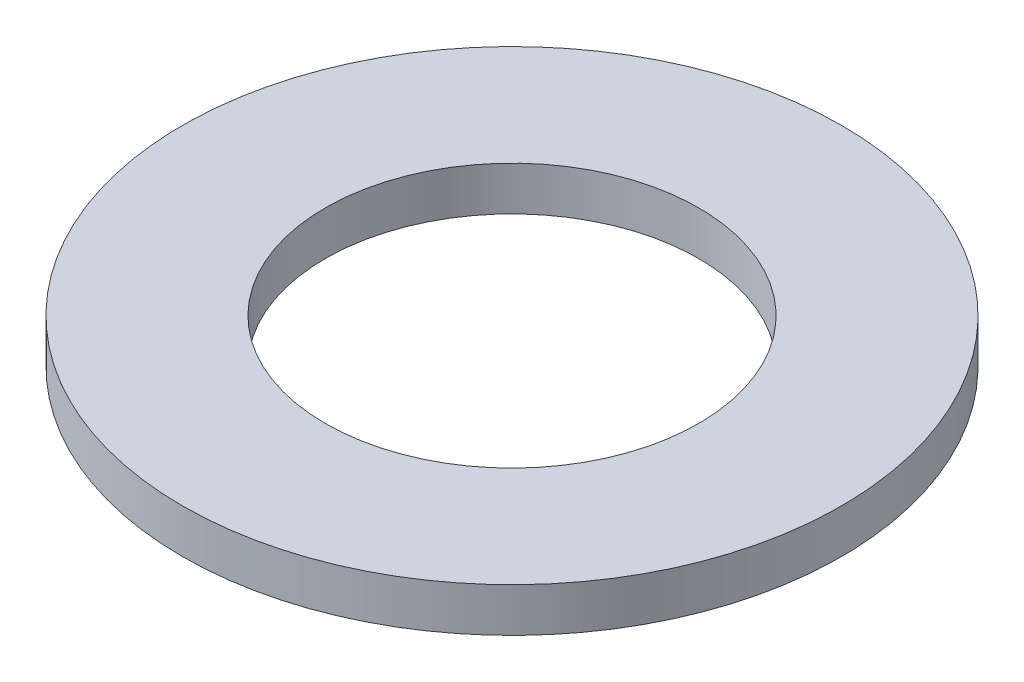
SolidWorks part; units mm, degrees
ref_plane "Front Plane" through (0, 0, 0) normal (0, 0, 1) x (1, 0, 0)
ref_plane "Top Plane" through (0, 0, 0) normal (0, 1, 0) x (1, 0, 0)
ref_plane "Right Plane" through (0, 0, 0) normal (1, 0, 0) x (0, 0, -1)
sketch "Sketch1" plane through (0, 0, 0) normal (0, 1, 0) x (1, 0, 0)
  circle A0 centre (0, 0) radius 7.5
  circle A1 centre (0, 0) radius 4.25
extrude "Boss-Extrude1" add sketch "Sketch1" along normal blind 1
